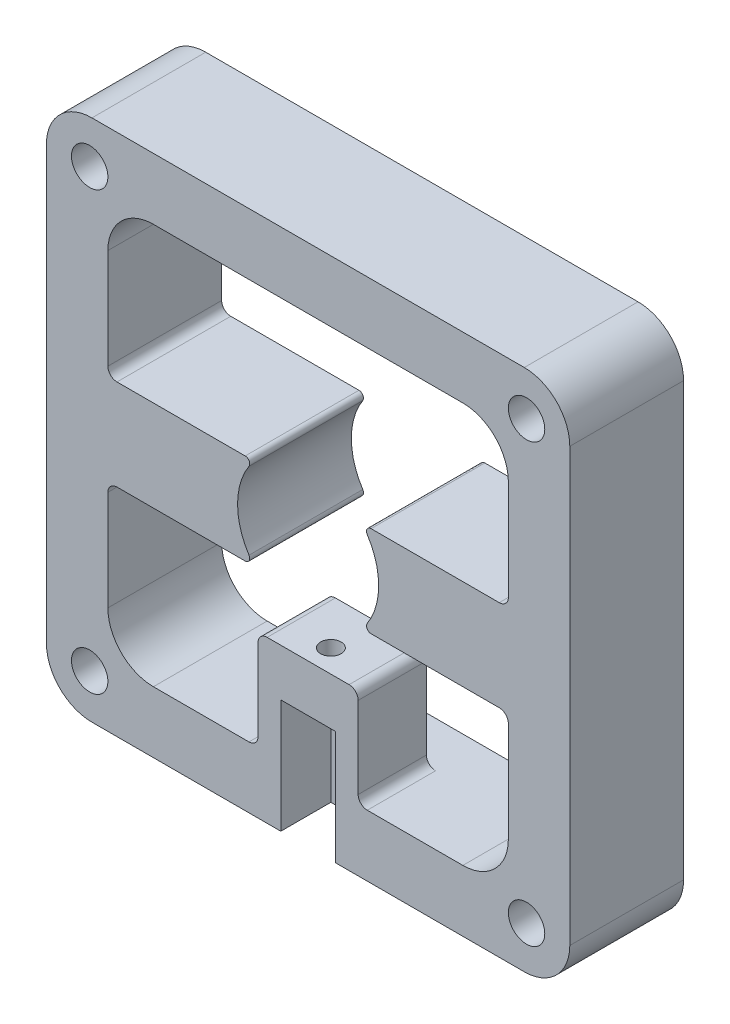
SolidWorks part; units mm, degrees
ref_plane "Front Plane" through (0, 0, 0) normal (0, 0, 1) x (1, 0, 0)
ref_plane "Top Plane" through (0, 0, 0) normal (0, 1, 0) x (1, 0, 0)
ref_plane "Right Plane" through (0, 0, 0) normal (1, 0, 0) x (0, 0, -1)
sketch "Sketch1" plane through (0, 0, 0) normal (0, 0, 1) x (1, 0, 0)
  line L1 (57.5, -57.5) -> (-57.5, -57.5)
  line L2 (57.5, -57.5) -> (57.5, 57.5)
  line L3 (57.5, 57.5) -> (-57.5, 57.5)
  line L4 (-57.5, -57.5) -> (-57.5, 57.5)
  line L5 (57.5, -57.5) -> (-57.5, 57.5) construction
  line L6 (57.5, 57.5) -> (-57.5, -57.5) construction
  point P0 (0, 0)
  dimension "D1" = 115
  dimension "D2" = 115
extrude "Boss-Extrude1" add sketch "Sketch1" along normal mid plane 25
ref_plane "Plane1" through (0, 0, 12.5) normal (0, 0, 1) x (1, 0, 0)
sketch "Sketch2" plane through (0, 0, 12.5) normal (0, 0, 1) x (1, 0, 0)
  circle A0 centre (-48, 48) radius 4
  circle A1 centre (48, 48) radius 4
  circle A2 centre (48, -48) radius 4
  circle A3 centre (-48, -48) radius 4
  point P12 (0, 0)
  dimension "D1" = 8
  dimension "D2" = 48
  dimension "D3" = 48
  dimension "D4" = 4
extrude "Cut-Extrude1" cut sketch "Sketch2" against normal blind 30
fillet "Fillet1" radius 10 4 edges at (-57.5, -57.5, 0) (57.5, -57.5, 0) (57.5, 57.5, 0) (-57.5, 57.5, 0)
sketch "Sketch3" plane through (0, 0, 12.5) normal (0, 0, 1) x (1, 0, 0)
  line L0 (0, 0) -> (71.9323, 71.9323) construction
  line L1 (12.9476, 24.2613) -> (33.6863, 45)
  line L4 (33.6863, -45) -> (-33.6863, -45)
  line L5 (45, -33.6863) -> (45, 33.6863)
  line L6 (33.6863, 45) -> (-33.6863, 45)
  line L7 (-45, -33.6863) -> (-45, 33.6863)
  line L8 (45, -45) -> (-45, 45) construction
  line L9 (45, 45) -> (-45, -45) construction
  line L10 (24.2613, -12.9476) -> (45, -33.6863)
  line L11 (24.2613, 12.9476) -> (45, 33.6863)
  line L12 (-12.9476, -24.2613) -> (-33.6863, -45)
  line L13 (12.9476, -24.2613) -> (33.6863, -45)
  line L14 (-12.9476, 24.2613) -> (-33.6863, 45)
  line L15 (-24.2613, 12.9476) -> (-45, 33.6863)
  line L16 (-24.2613, -12.9476) -> (-45, -33.6863)
  circle A0 centre (0, 0) radius 16.5
  arc A1 (12.9476, 24.2613) -> (-12.9476, 24.2613) centre (0, 0) ccw
  arc A2 (-24.2613, 12.9476) -> (-24.2613, -12.9476) centre (0, 0) ccw
  arc A3 (24.2613, -12.9476) -> (24.2613, 12.9476) centre (0, 0) ccw
  arc A4 (-12.9476, -24.2613) -> (12.9476, -24.2613) centre (0, 0) ccw
  point P28 (0, 0)
  dimension "D1" = 33
  dimension "D2" = 55
  dimension "D3" = 8
  dimension "D4" = 90
  dimension "D5" = 90
extrude "Cut-Extrude2" [suppressed] cut sketch "Sketch3" against normal blind 30
fillet "Fillet2" [suppressed] radius 2
sketch "Sketch4" [suppressed] plane through (0, 0, 15) normal (0, 0, 1) x (1, 0, 0)
  line L1 (-35.3876, 39.5599) -> (35.3876, 39.5599)
  line L2 (-35.3876, 39.5599) -> (-35.3876, 17.9256)
  line L3 (-35.3876, 17.9256) -> (35.3876, 17.9256)
  line L4 (35.3876, 39.5599) -> (35.3876, 17.9256)
  line L5 (-35.3876, 39.5599) -> (35.3876, 17.9256) construction
  line L6 (-35.3876, 17.9256) -> (35.3876, 39.5599) construction
  circle A0 centre (0, 0) radius 15.24
  point P3 (0, 28.7428)
  dimension "D1" = 30.48
sketch "Sketch5" plane through (0, 0, 12.5) normal (0, 0, 1) x (1, 0, 0)
  line L1 (44, -44) -> (-44, -44)
  line L2 (44, -44) -> (44, 44)
  line L3 (44, 44) -> (-44, 44)
  line L4 (-44, -44) -> (-44, 44)
  line L5 (44, -44) -> (-44, 44) construction
  line L6 (44, 44) -> (-44, -44) construction
  point P0 (0, 0)
  dimension "D1" = 88
extrude "Cut-Extrude3" cut sketch "Sketch5" against normal blind 30
fillet "Fillet4" radius 10 4 edges at (44, -44, 0) (-44, -44, 0) (44, 44, 0) (-44, 44, 0)
sketch "Sketch6" plane through (0, 0, 12.5) normal (0, 0, 1) x (1, 0, 0)
  line L0 (-44, 34) -> (-44, -34) construction
  line L1 (44, -10) -> (-44, -10)
  line L2 (44, -10) -> (44, 10)
  line L3 (44, 10) -> (-44, 10)
  line L4 (-44, -10) -> (-44, 10)
  line L5 (44, -10) -> (-44, 10) construction
  line L6 (44, 10) -> (-44, -10) construction
  line L7 (0, 60.2671) -> (0, -62.585) construction
  point P0 (0, 0)
  dimension "D1" = 20
extrude "Boss-Extrude2" add sketch "Sketch6" against normal blind 25
sketch "Sketch10" plane through (0, 0, 12.5) normal (0, 0, 1) x (1, 0, 0)
  line L1 (19, -6) -> (-19, -6)
  line L2 (19, -6) -> (19, -44)
  line L3 (19, -44) -> (-19, -44)
  line L4 (-19, -6) -> (-19, -44)
  line L5 (19, -6) -> (-19, -44) construction
  line L6 (19, -44) -> (-19, -6) construction
  point P0 (0, -25)
  dimension "D1" = 25
  dimension "D2" = 38
  dimension "D3" = 38
extrude "Boss-Extrude4" [suppressed] add sketch "Sketch10" against normal blind 20
sketch "Sketch11" plane through (0, 0, 12.5) normal (0, 0, 1) x (1, 0, 0)
  circle A0 centre (0, 0) radius 22.5
  dimension "D1" = 45
extrude "Boss-Extrude5" [suppressed] add sketch "Sketch11" against normal blind 20
sketch "Sketch12" plane through (0, 0, 12.5) normal (0, 0, 1) x (1, 0, 0)
  circle A0 centre (0, 0) radius 15.5
  dimension "D1" = 31
extrude "Cut-Extrude5" [suppressed] cut sketch "Sketch12" against normal blind 20
ref_plane "Plane2" through (0, -22.1, 0) normal (0, -1, 0) x (-1, 0, 0)
sketch "Sketch14" plane through (0, -22.1, 0) normal (0, -1, 0) x (-1, 0, 0)
  line L1 (11, 2.5) -> (-11, 2.5)
  line L2 (11, 2.5) -> (11, -12.5)
  line L3 (11, -12.5) -> (-11, -12.5)
  line L4 (-11, 2.5) -> (-11, -12.5)
  line L5 (11, 2.5) -> (-11, -12.5) construction
  line L6 (11, -12.5) -> (-11, 2.5) construction
  point P0 (0, -5)
  dimension "D1" = 5
  dimension "D2" = 15
  dimension "D3" = 22
extrude "Boss-Extrude6" add sketch "Sketch14" along normal blind 30
sketch "Sketch15" plane through (0, 0, 12.5) normal (0, 0, 1) x (1, 0, 0)
  line L0 (0, 0) -> (0, -36.0044) construction
  line L2 (-22.5, -8.1) -> (22.5, -8.1)
  line L3 (-22.5, -8.1) -> (-22.5, -20.1)
  line L4 (-22.5, -20.1) -> (22.5, -20.1)
  line L5 (22.5, -8.1) -> (22.5, -20.1)
  line L6 (-22.5, -8.1) -> (22.5, -20.1) construction
  line L7 (-22.5, -20.1) -> (22.5, -8.1) construction
  point P3 (0, -14.1)
  dimension "D1" = 20.1
  dimension "D2" = 12
  dimension "D3" = 45
extrude "Cut-Extrude6" [suppressed] cut sketch "Sketch15" against normal blind 30
sketch "Sketch16" plane through (0, 0, 12.5) normal (0, 0, 1) x (1, 0, 0)
  circle A0 centre (0, 0) radius 15.5
  dimension "D1" = 31
extrude "Cut-Extrude7" cut sketch "Sketch16" against normal blind 30
fillet "Fillet6" radius 1 4 edges at (11.8427, -10, 0) (-11.8427, -10, 0) (11.8427, 10, 0) (-11.8427, 10, 0)
fillet "Fillet8" radius 2 8 edges at (-11, -44, 5) (11, -44, 5) (11, -22.1, 5) (-11, -22.1, 5) (44, -10, 0) (-44, -10, 0) (-44, 10, 0) (44, 10, 0)
ref_plane "Plane3" through (0, -22.1, 0) normal (0, 1, 0) x (1, 0, 0)
sketch "Sketch17" plane through (0, -22.1, 0) normal (0, 1, 0) x (1, 0, 0)
  circle A0 centre (0, -7.5) radius 2.25
  dimension "D2" = 4.5
  dimension "D1" = 7.5
extrude "Cut-Extrude8" cut sketch "Sketch17" against normal blind 40
ref_plane "Plane4" through (0, -57.5, 0) normal (0, -1, 0) x (-1, 0, 0)
sketch "Sketch18" plane through (0, -57.5, 0) normal (0, -1, 0) x (-1, 0, 0)
  line L0 (0, 15.8478) -> (0, -17.6328) construction
  line L2 (-6, -1.5) -> (6, -1.5)
  line L3 (-6, -1.5) -> (-6, -13.5)
  line L4 (-6, -13.5) -> (6, -13.5)
  line L5 (6, -1.5) -> (6, -13.5)
  line L6 (-6, -1.5) -> (6, -13.5) construction
  line L7 (-6, -13.5) -> (6, -1.5) construction
  point P2 (0, -7.5)
  dimension "D1" = 7.5
  dimension "D2" = 12
  dimension "D3" = 12
extrude "Cut-Extrude9" cut sketch "Sketch18" against normal blind 25
